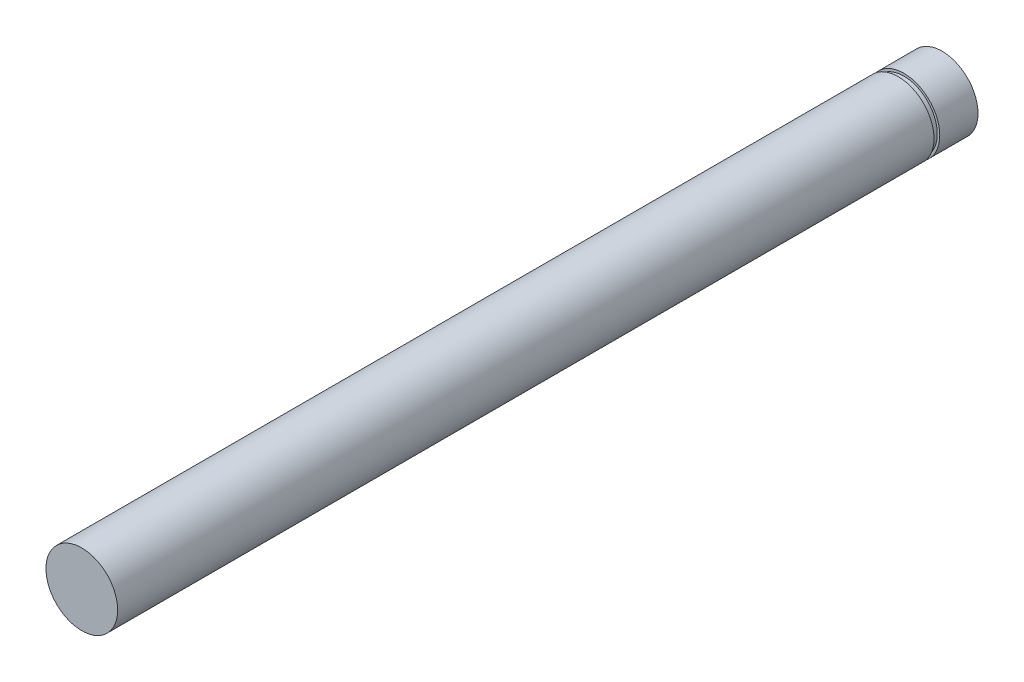
SolidWorks part; units mm, degrees
ref_plane "Front Plane" through (0, 0, 0) normal (0, 0, 1) x (1, 0, 0)
ref_plane "Top Plane" through (0, 0, 0) normal (0, 1, 0) x (1, 0, 0)
ref_plane "Right Plane" through (0, 0, 0) normal (1, 0, 0) x (0, 0, -1)
sketch "Sketch1" plane through (0, 0, 0) normal (0, 0, 1) x (1, 0, 0)
  circle A0 centre (0, 0) radius 2.3813
extrude "Boss-Extrude1" add sketch "Sketch1" against normal blind 57.15
sketch "Sketch2" [suppressed] plane through (0, 0, 0) normal (1, 0, 0) x (0, 0, -1)
  circle A0 centre (4.4812, 0) radius 0.8001
  circle A1 centre (31.9439, 0) radius 0.8001
extrude "Cut-Extrude1" [suppressed] cut sketch "Sketch2" against normal through all and the other way through all
sketch "Sketch4" plane through (0, 0, -57.15) normal (0, 0, -1) x (-1, 0, 0)
  circle A0 centre (0, 0) radius 2.3813
  circle A1 centre (0, 0) radius 2.216
extrude "Cut-Extrude2" cut sketch "Sketch4" against normal blind 0.381 from offset 2.54 offset against normal yes
